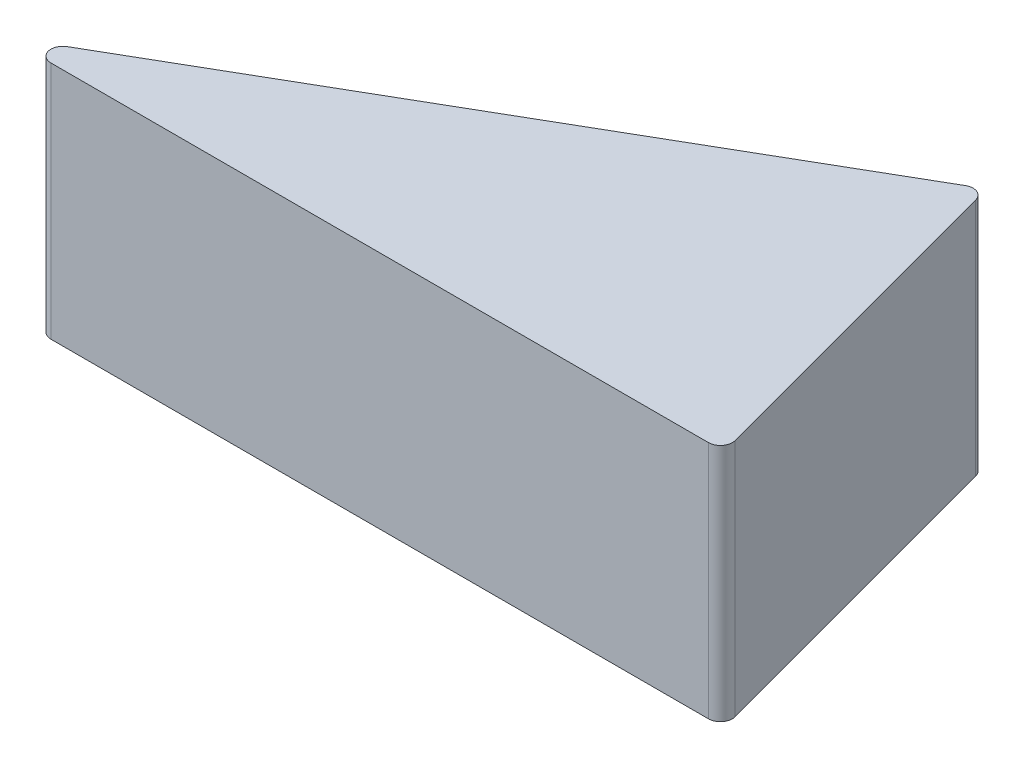
SolidWorks part; units mm, degrees
ref_plane "Front Plane" through (0, 0, 0) normal (0, 0, 1) x (1, 0, 0)
ref_plane "Top Plane" through (0, 0, 0) normal (0, 1, 0) x (1, 0, 0)
ref_plane "Right Plane" through (0, 0, 0) normal (1, 0, 0) x (0, 0, -1)
sketch "Sketch1" plane through (0, 0, 0) normal (0, 1, 0) x (1, 0, 0)
  line L1 (0, 0) -> (30, 0)
  line L2 (30, 0) -> (25.9808, 15)
  line L3 (25.9808, 15) -> (0, 0)
  point P0 (8.3602, -0.4129)
  dimension "D1" = 30
  dimension "D2" = 30
  dimension "D3" = 30
extrude "Boss-Extrude1" add sketch "Sketch1" along normal blind 10
fillet "Fillet1" radius 0.5 3 edges at (30, 5, 0) (25.9808, 5, -15) (0, 5, 0)
